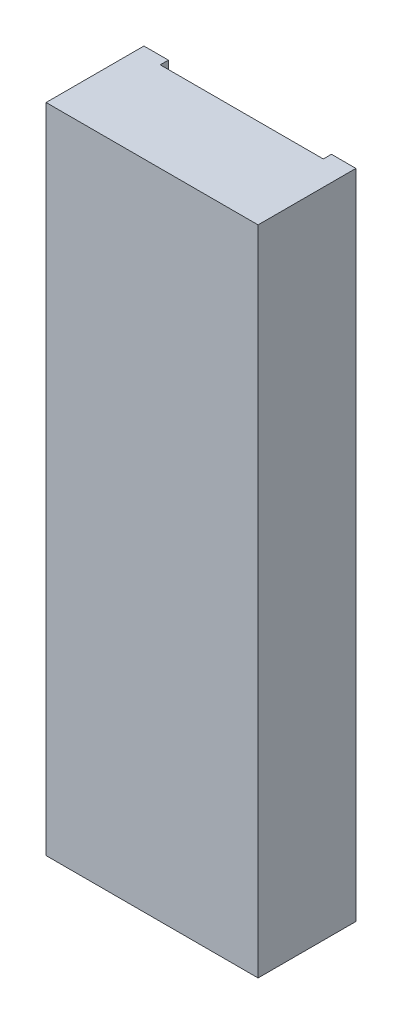
SolidWorks part; units mm, degrees
ref_plane "Front Plane" through (0, 0, 0) normal (0, 0, 1) x (1, 0, 0)
ref_plane "Top Plane" through (0, 0, 0) normal (0, 1, 0) x (1, 0, 0)
ref_plane "Right Plane" through (0, 0, 0) normal (1, 0, 0) x (0, 0, -1)
sketch "Sketch1" plane through (0, 0, 0) normal (0, 0, 1) x (1, 0, 0)
  line L1 (-65, 200) -> (65, 200)
  line L2 (-65, 200) -> (-65, -200)
  line L3 (-65, -200) -> (65, -200)
  line L4 (65, 200) -> (65, -200)
  line L5 (-65, 200) -> (65, -200) construction
  line L6 (-65, -200) -> (65, 200) construction
  point P0 (0, 0)
  dimension "D1" = 400
  dimension "D2" = 130
extrude "Boss-Extrude1" add sketch "Sketch1" along normal blind 60
sketch "Sketch2" plane through (0, 0, 0) normal (0, 0, -1) x (-1, 0, 0)
  line L0 (65, -200) -> (-65, -200) construction
  line L1 (-50, 200) -> (50, 200)
  line L2 (-50, 200) -> (-50, -200)
  line L3 (-50, -200) -> (50, -200)
  line L4 (50, 200) -> (50, -200)
  line L5 (-50, 200) -> (50, -200) construction
  line L6 (-50, -200) -> (50, 200) construction
  point P0 (0, 0)
  dimension "D1" = 100
extrude "Cut-Extrude1" cut sketch "Sketch2" against normal blind 5
